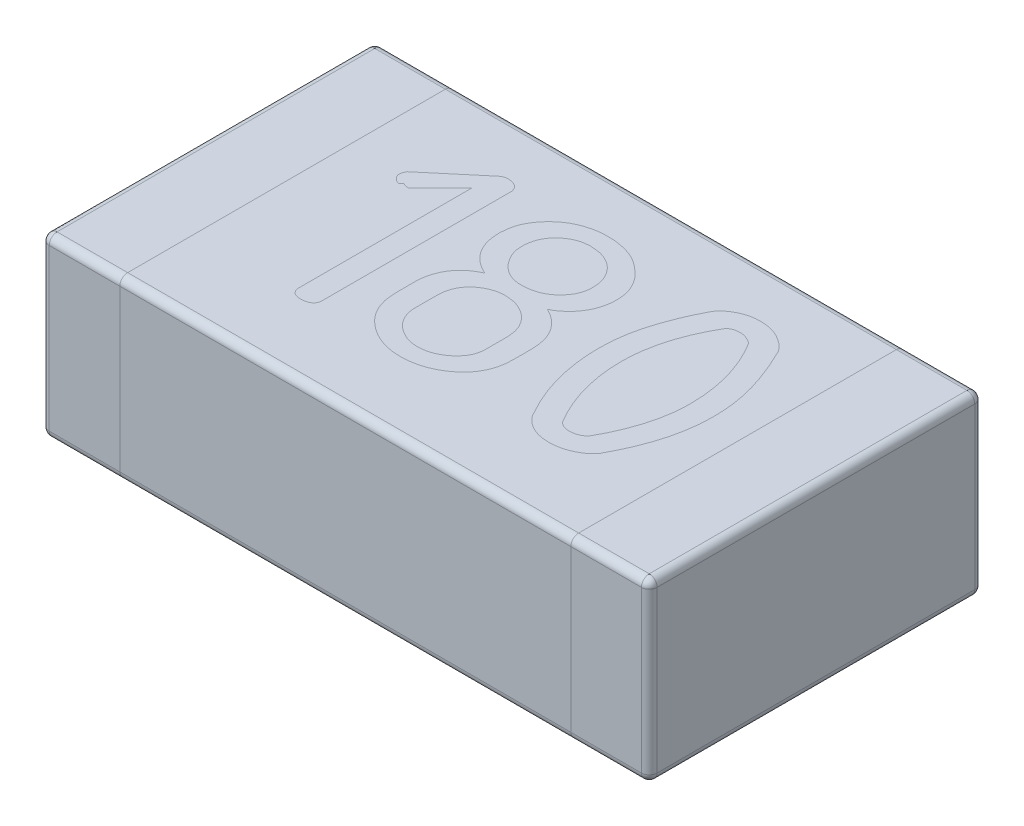
SolidWorks part; units mm, degrees
ref_plane "Front Plane" through (0, 0, 0) normal (0, 0, 1) x (1, 0, 0)
ref_plane "Top Plane" through (0, 0, 0) normal (0, 1, 0) x (1, 0, 0)
ref_plane "Right Plane" through (0, 0, 0) normal (1, 0, 0) x (0, 0, -1)
sketch "Sketch1" plane through (0, 0, 0) normal (0, 1, 0) x (1, 0, 0)
  line L1 (-0.755, -0.425) -> (0.755, -0.425)
  line L2 (-0.775, -0.405) -> (-0.775, 0.405)
  line L3 (-0.755, 0.425) -> (0.755, 0.425)
  line L4 (0.775, -0.405) -> (0.775, 0.405)
  line L5 (-0.775, -0.425) -> (0.775, 0.425) construction
  line L6 (-0.775, 0.425) -> (0.775, -0.425) construction
  arc A4 (-0.775, -0.405) -> (-0.755, -0.425) centre (-0.755, -0.405) ccw
  arc A5 (0.755, -0.425) -> (0.775, -0.405) centre (0.755, -0.405) ccw
  arc A6 (0.775, 0.405) -> (0.755, 0.425) centre (0.755, 0.405) ccw
  arc A7 (-0.755, 0.425) -> (-0.775, 0.405) centre (-0.755, 0.405) ccw
  point P0 (0, 0)
  dimension "D4" = 0.02
  dimension "D1" = 1.55
  dimension "D2" = 0.85
extrude "Boss-Extrude1" add sketch "Sketch1" along normal mid plane 0.45
sketch "Sketch3" plane through (0, 0.225, 0) normal (0, 1, 0) x (1, 0, 0)
  line L0 (-0.575, 0) -> (0.575, 0) construction
  line L1 (-0.575, -0.5133) -> (-0.575, 0.5133)
  line L2 (0.575, -0.5133) -> (0.575, 0.5133)
  line L3 (0, -0.25) -> (0, 0.25) construction
  line L6 (-0.575, -0.25) -> (0.575, -0.25) construction
  text T0 "<b>180</b>\r\n" font "SWIsop1" height 0.53
  point P4 (0, 0)
  point P8 (-0.575, 0)
  point P11 (0.575, 0)
  point P14 (0, 0)
  point P17 (0, -0.25)
  dimension "D1" = 1.15
  dimension "D2" = 0.5
sketch "Sketch4" plane through (0, 0, 0.425) normal (0, 0, 1) x (1, 0, 0)
  line L0 (-0.575, 0.225) -> (-0.575, -0.5946)
  line L1 (0.575, 0.225) -> (0.575, -0.5946)
sketch "Sketch5" plane through (0, 0, -0.425) normal (0, 0, -1) x (-1, 0, 0)
  line L0 (-0.575, 0.225) -> (-0.575, -0.5946) construction
  line L1 (-0.575, 0.225) -> (-0.575, -0.5946)
  line L2 (0.575, 0.225) -> (0.575, -0.5946) construction
  line L3 (0.575, 0.225) -> (0.575, -0.5946)
sketch "Sketch6" plane through (0, -0.225, 0) normal (0, -1, 0) x (1, 0, 0)
  line L0 (0.575, 0.5133) -> (0.575, -0.5133) construction
  line L1 (-0.575, 0.5133) -> (-0.575, -0.5133) construction
  line L2 (0.575, 0.5133) -> (0.575, -0.5133)
  line L3 (-0.575, 0.5133) -> (-0.575, -0.5133)
split line "Split Line2"
split line "Split Line3"
split line "Split Line4"
split line "Split Line5"
fillet "Fillet2" radius 0.02 24 edges at (-0.665, -0.225, 0.425) (0, -0.225, 0.425) (0.665, -0.225, 0.425) (-0.7691, -0.225, 0.4191) (-0.775, -0.225, 0) (-0.7691, -0.225, -0.4191) (0.665, -0.225, -0.425) (0, -0.225, -0.425) (-0.665, -0.225, -0.425) (0.7691, -0.225, -0.4191) (0.775, -0.225, 0) (0.7691, -0.225, 0.4191) (-0.7691, 0.225, 0.4191) (-0.775, 0.225, 0) (-0.7691, 0.225, -0.4191) (0.665, 0.225, -0.425) (0, 0.225, -0.425) (-0.665, 0.225, -0.425) (0.7691, 0.225, -0.4191) (0.775, 0.225, 0) (0.7691, 0.225, 0.4191) (-0.665, 0.225, 0.425) (0, 0.225, 0.425) (0.665, 0.225, 0.425)
